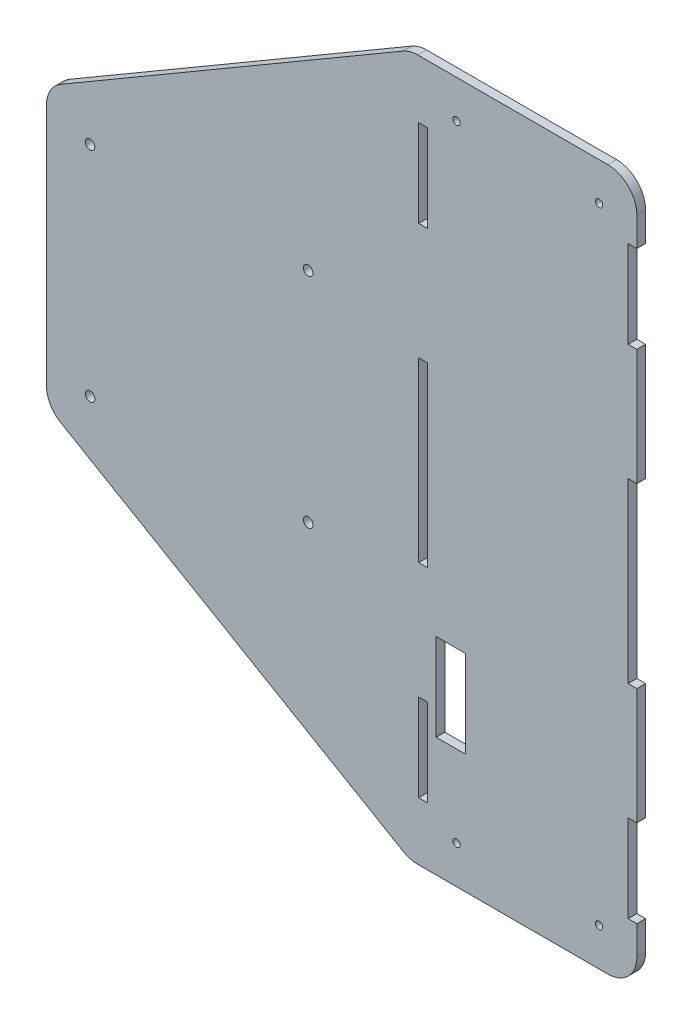
SolidWorks part; units mm, degrees
material "ABS"
ref_plane "前视基准面" through (0, 0, 0) normal (0, 0, 1) x (1, 0, 0)
ref_plane "上视基准面" through (0, 0, 0) normal (0, 1, 0) x (1, 0, 0)
ref_plane "右视基准面" through (0, 0, 0) normal (1, 0, 0) x (0, 0, -1)
sketch "草图1" plane through (0, 0, 0) normal (0, 0, 1) x (1, 0, 0)
  line L1 (-1.8252, 96.4322) -> (76.1748, 96.4322)
  line L2 (-1.8252, 96.4322) -> (-1.8252, -144.5678)
  line L3 (-1.8252, -144.5678) -> (76.1748, -144.5678)
  line L4 (76.1748, 96.4322) -> (76.1748, -144.5678)
  dimension "D1" = 78
  dimension "D2" = 241
extrude "凸台-拉伸1" add sketch "草图1" against normal blind 3 contours L4 L3 L2 L1
sketch "草图2" plane through (0, 0, 0) normal (0, 0, 1) x (1, 0, 0)
  line L0 (-1.8252, 96.4322) -> (-126.8252, 23.4322)
  line L1 (-126.8252, 23.4322) -> (-126.8252, -71.5678)
  line L2 (-126.8252, -71.5678) -> (-1.8252, -144.5678)
  line L3 (-1.8252, -144.5678) -> (-1.8252, 96.4322)
  line L4 (-1.8252, -144.5678) -> (76.1748, -144.5678) construction
  dimension "D1" = 95
  dimension "D2" = 241
  dimension "D3" = 73
  dimension "D4" = 125
  dimension "D5" = 73
extrude "凸台-拉伸2" add sketch "草图2" against normal blind 3
sketch "草图5" plane through (0, 0, 0) normal (0, 0, 1) x (1, 0, 0)
  line L0 (-126.8252, -24.0678) -> (76.1748, -24.0678) construction
  line L1 (-126.8252, 23.4322) -> (-126.8252, -71.5678) construction
  line L2 (76.1748, 96.4322) -> (76.1748, -144.5678) construction
  line L3 (76.1748, 76.4322) -> (73.1748, 76.4322)
  line L4 (76.1748, -124.5678) -> (73.1748, -124.5678)
  line L5 (76.1748, -124.5678) -> (76.1748, -94.5678)
  line L6 (76.1748, -94.5678) -> (73.1748, -94.5678)
  line L7 (73.1748, -124.5678) -> (73.1748, -94.5678)
  line L9 (76.1748, 6.4322) -> (76.1748, -54.5678)
  line L10 (76.1748, -54.5678) -> (73.1748, -54.5678)
  line L11 (73.1748, 6.4322) -> (73.1748, -54.5678)
  line L12 (76.1748, 76.4322) -> (76.1748, 46.4322)
  line L13 (73.1748, 76.4322) -> (73.1748, 46.4322)
  line L14 (76.1748, 46.4322) -> (73.1748, 46.4322)
  line L15 (76.1748, 6.4322) -> (73.1748, 6.4322)
  dimension "D1" = 20
  dimension "D2" = 30
  dimension "D3" = 3
  dimension "D4" = 40
extrude "切除-拉伸3" cut sketch "草图5" against normal blind 3
sketch "草图6" plane through (0, 0, -3) normal (0, 0, -1) x (-1, 0, 0)
  line L1 (-1.1748, 76.4322) -> (-4.1748, 76.4322)
  line L2 (-1.1748, 76.4322) -> (-1.1748, 46.4322)
  line L3 (-1.1748, 46.4322) -> (-4.1748, 46.4322)
  line L4 (-4.1748, 76.4322) -> (-4.1748, 46.4322)
  line L5 (-1.1748, 6.4322) -> (-4.1748, 6.4322)
  line L6 (-1.1748, 6.4322) -> (-1.1748, -54.5678)
  line L7 (-1.1748, -54.5678) -> (-4.1748, -54.5678)
  line L8 (-4.1748, 6.4322) -> (-4.1748, -54.5678)
  line L9 (-1.1748, -94.5678) -> (-4.1748, -94.5678)
  line L10 (-1.1748, -94.5678) -> (-1.1748, -124.5678)
  line L11 (-1.1748, -124.5678) -> (-4.1748, -124.5678)
  line L12 (-4.1748, -94.5678) -> (-4.1748, -124.5678)
extrude "切除-拉伸4" cut sketch "草图6" against normal blind 3
sketch "草图7" plane through (0, 0, 0) normal (0, 0, 1) x (1, 0, 0)
  line L0 (4.1748, -94.5678) -> (4.1748, -54.5678) construction
  line L1 (7.1748, -73.5678) -> (17.1748, -73.5678)
  line L2 (7.1748, -73.5678) -> (7.1748, -103.5678)
  line L3 (7.1748, -103.5678) -> (17.1748, -103.5678)
  line L4 (17.1748, -73.5678) -> (17.1748, -103.5678)
  line L5 (31.1748, -118.5678) -> (73.1748, -118.5678) construction
  dimension "D1" = 3
  dimension "D2" = 10
  dimension "D3" = 30
  dimension "D4" = 15
extrude "切除-拉伸5" cut sketch "草图7" against normal blind 3
fillet "圆角1" radius 10 6 edges at (76.1748, 96.4322, -1.5) (76.1748, -144.5678, -1.5) (-1.8252, -144.5678, -1.5) (-126.8252, -71.5678, -1.5) (-126.8252, 23.4322, -1.5) (-1.8252, 96.4322, -1.5)
hole_wizard "M4 螺纹孔的螺纹孔钻头1" positions "3D草图4" profile "草图11" hole size "M4" standard "AS" end condition through all
sketch3d "3D草图4"
  line L0 (-126.8252, 17.6918, -3) -> (-126.8252, -65.8274, -3) construction
  line L1 (-126.8252, 13.4322, -3) -> (76.1748, 13.4322, -3) construction
  line L2 (76.1748, 46.4322, -3) -> (76.1748, 6.4322, -3) construction
  line L4 (-126.8252, -61.5678, -3) -> (76.1748, -61.5678, -3) construction
  line L5 (76.1748, -54.5678, -3) -> (76.1748, -94.5678, -3) construction
  line L7 (0.8809, 96.4322, -3) -> (66.1748, 96.4322, -3) construction
  line L8 (0.8809, -144.5678, -3) -> (66.1748, -144.5678, -3) construction
  point P0 (-111.8252, 13.4322, -3)
  point P2 (-111.8252, -61.5678, -3)
  point P4 (-36.8252, -61.5678, -3)
  point P6 (-36.8252, 13.4322, -3)
  dimension "D1" = 15
  dimension "D2" = 15
  dimension "D3" = 75
  dimension "D4" = 75
  dimension "D5" = 75
  dimension "D6" = 75
  dimension "D7" = 75
  dimension "D8" = 0
  dimension "D9" = 0
  dimension "D10" = 83
  dimension "D11" = 83
sketch "草图11" plane through (-111.8252, 13.4322, -3) normal (1, 0, 0) x (0, 1, 0)
  line L0 (0, 0) -> (0, 3)
  line L1 (0, 3) -> (1.65, 3)
  line L2 (1.65, 3) -> (1.65, 0)
  line L5 (1.65, 0) -> (0, 0)
  line L11 (0, -6.35) -> (0, 107.95) construction
  dimension "通孔孔直径" = 3.3
  dimension "通孔孔深度" = 3
hole_wizard "M3 螺纹孔的螺纹孔钻头2" positions "3D草图5" profile "草图17" hole size "M3" standard "AS" end condition through all
sketch3d "3D草图5"
  line L0 (0.8809, -144.5678, -3) -> (66.1748, -144.5678, -3) construction
  line L1 (76.1748, -124.5678, -3) -> (76.1748, -134.5678, -3) construction
  line L2 (0.8809, 96.4322, -3) -> (66.1748, 96.4322, -3) construction
  line L3 (76.1748, 86.4322, -3) -> (76.1748, 76.4322, -3) construction
  point P0 (63.1748, -131.5678, -3)
  point P2 (14.1748, -131.5678, -3)
  point P4 (63.1748, 83.4322, -3)
  point P6 (14.1748, 83.4322, -3)
  dimension "D1" = 13
  dimension "D2" = 13
  dimension "D3" = 13
  dimension "D4" = 62
  dimension "D5" = 13
  dimension "D6" = 13
  dimension "D7" = 49
  dimension "D8" = 13
sketch "草图17" plane through (63.1748, -131.5678, -3) normal (1, 0, 0) x (0, 1, 0)
  line L0 (0, 0) -> (0, 3)
  line L1 (0, 3) -> (1.25, 3)
  line L2 (1.25, 3) -> (1.25, 0)
  line L5 (1.25, 0) -> (0, 0)
  line L11 (0, -6.35) -> (0, 107.95) construction
  dimension "通孔孔直径" = 2.5
  dimension "通孔孔深度" = 3
